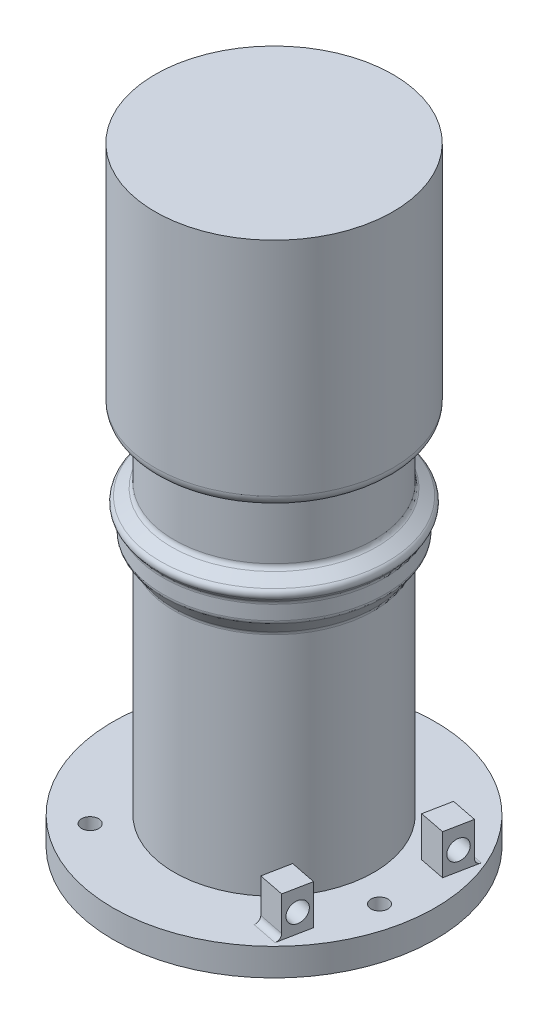
SolidWorks part; units mm, degrees
ref_plane "Front Plane" through (0, 0, 0) normal (0, 0, 1) x (1, 0, 0)
ref_plane "Top Plane" through (0, 0, 0) normal (0, 1, 0) x (1, 0, 0)
ref_plane "Right Plane" through (0, 0, 0) normal (1, 0, 0) x (0, 0, -1)
sketch "Sketch2" plane through (0, 0, 0) normal (0, 0, 1) x (1, 0, 0)
  line L0 (0, 0) -> (0, 156.5772) construction
  line L1 (44.45, 101.6) -> (49.4542, 108.957)
  line L2 (49.4542, 108.957) -> (49.4542, 116.953)
  line L3 (49.4542, 116.953) -> (52.9525, 121.4508)
  line L4 (52.9525, 121.4508) -> (44.45, 126.7815)
  line L6 (44.45, 126.7815) -> (44.45, 152.1815)
  line L7 (44.45, 152.1815) -> (52.9525, 157.3455)
  line L8 (52.9525, 157.3455) -> (52.9525, 258.9455)
  line L9 (52.9525, 258.9455) -> (0, 258.9455)
  line L10 (0, 0) -> (44.45, 0)
  line L11 (0, 0) -> (0, 258.9455)
  line L12 (44.45, 0) -> (44.45, 101.6)
  point P3 (44.45, 0)
  point P4 (44.45, 101.6)
  point P5 (49.4542, 108.957)
  point P6 (49.4542, 116.953)
  point P7 (52.9525, 121.4508)
  point P9 (44.45, 126.7815)
  point P10 (44.45, 152.1815)
  point P11 (52.9525, 157.3455)
  point P12 (52.9525, 258.9455)
  dimension "D1" = 101.6
  dimension "D2" = 8.8977
  dimension "D3" = 7.996
  dimension "D4" = 10.0354
  dimension "D5" = 5.698
  dimension "D6" = 25.4
  dimension "D7" = 9.9479
  dimension "D8" = 101.6
  dimension "D9" = 44.45
revolve "Revolve1" add sketch "Sketch2" angle 360 about L0
sketch "Sketch3" plane through (0, 0, 0) normal (0, -1, 0) x (-1, 0, 0)
  circle A0 centre (0, 0) radius 71.755
  dimension "D1" = 143.51
extrude "Boss-Extrude1" add sketch "Sketch3" along normal blind 12.192
sketch "Sketch5" plane through (0, -12.192, 0) normal (0, -1, 0) x (-1, 0, 0)
  circle A0 centre (37.5252, -44.3557) radius 3.81
  circle A1 centre (-57.8789, -10.9246) radius 3.81
  circle A2 centre (18.7753, 54.9823) radius 3.81
  point P9 (-0.5261, -0.0993)
  dimension "D2" = 101.092
  dimension "D3" = 7.62
  dimension "D1" = 3
extrude "Cut-Extrude1" cut sketch "Sketch5" against normal up to surface (12.192 mm away) up to face at (0, 0, -44.45)
sketch "Sketch6" plane through (0, 0, 0) normal (0, 1, 0) x (1, 0, 0)
  line L0 (57.8789, -10.9246) -> (70.4892, -13.4182) construction
  line L1 (57.8789, -10.9246) -> (46.1709, -8.6094) construction
  line L2 (51.2763, -9.6189) -> (40.6568, -63.3215) construction
  line L3 (51.2763, -9.6189) -> (60.084, 34.9218) construction
  line L4 (50.2165, 15.5018) -> (61.8175, 13.2077)
  line L5 (38.3909, -44.3002) -> (49.9918, -46.5942)
  line L6 (38.3909, -44.3002) -> (40.7351, -32.4456)
  line L7 (40.7351, -32.4456) -> (52.336, -34.7397)
  line L8 (49.9918, -46.5942) -> (52.336, -34.7397)
  line L9 (38.3909, -44.3002) -> (52.336, -34.7397) construction
  line L10 (40.7351, -32.4456) -> (49.9918, -46.5942) construction
  line L11 (52.5607, 27.3564) -> (50.2165, 15.5018)
  line L12 (52.5607, 27.3564) -> (61.8175, 13.2077) construction
  line L13 (50.2165, 15.5018) -> (64.1617, 25.0623) construction
  line L14 (52.5607, 27.3564) -> (64.1617, 25.0623)
  line L15 (64.1617, 25.0623) -> (61.8175, 13.2077)
  circle A0 centre (0, 0) radius 71.755 construction
  point P11 (47.3513, -30.1142)
  point P12 (45.3635, -39.5199)
  point P13 (45.3635, -39.5199)
  dimension "D1" = 30.48
extrude "Boss-Extrude2" add sketch "Sketch6" along normal blind 17.78
sketch "Sketch7" plane through (56.9777, 0, 11.2671) normal (0.981, 0, 0.194) x (0.194, 0, -0.981)
  line L0 (-36.0112, 8.382) -> (-23.9271, 8.382) construction
  line L1 (-36.0112, 17.78) -> (-36.0112, 0) construction
  line L2 (-23.9271, 17.78) -> (-23.9271, 0) construction
  line L3 (-36.0112, 0) -> (-23.9271, 0) construction
  circle A0 centre (-29.9691, 8.382) radius 4.445
  point P10 (-29.9691, 0)
  dimension "D2" = 8.89
  dimension "D1" = 8.382
extrude "Cut-Extrude2" cut sketch "Sketch7" against normal up to surface (11.8256 mm away) up to face at (39.563, 8.89, 38.3729)
ref_plane "Plane1" through (0.0991, 0, -0.5012) normal (-0.194, 0, 0.981) x (0.981, 0, 0.194)
fillet "Fillet1" radius 2.54 1 edges at (44.1914, 0, 45.4472)
mirror "Mirror1" about plane through (0.0991, 0, -0.5012) normal (-0.194, 0, 0.981) of "Cut-Extrude2"
fillet "Fillet2" radius 2.54 1 edges at (58.3612, 0, -26.2094)
fillet "Fillet3" radius 2.54 5 edges at (0, 126.7815, -44.45) (0, 121.4508, -52.9525) (0, 116.953, -49.4542) (0, 108.957, -49.4542) (0, 101.6, -44.45)
fillet "Fillet4" radius 5.08 1 edges at (0, 157.3455, -52.9525)
sketch "Sketch8" plane through (0, -12.192, 0) normal (0, -1, 0) x (-1, 0, 0)
  circle A0 centre (0, 0) radius 37.8612
extrude "Cut-Extrude3" cut sketch "Sketch8" against normal blind 25.4
